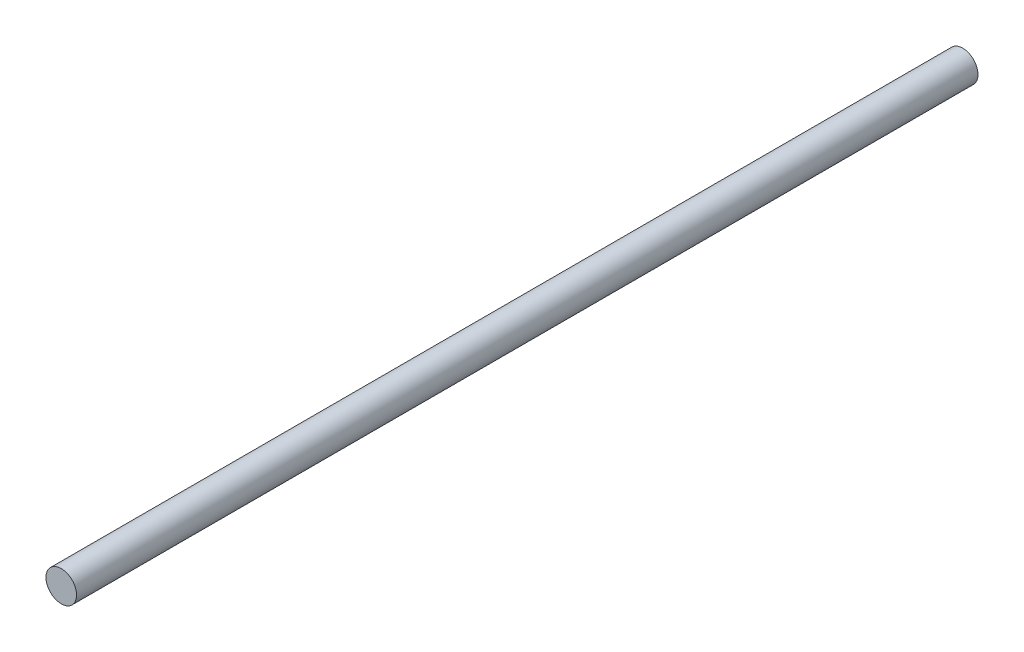
SolidWorks part; units mm, degrees
ref_plane "Ön Düzlem" through (0, 0, 0) normal (0, 0, 1) x (1, 0, 0)
ref_plane "Üst Düzlem" through (0, 0, 0) normal (0, 1, 0) x (1, 0, 0)
ref_plane "Sağ Düzlem" through (0, 0, 0) normal (1, 0, 0) x (0, 0, -1)
sketch "Sketch1" plane through (0, 0, 0) normal (0, 0, 1) x (1, 0, 0)
  circle A0 centre (0, 0) radius 1.95
extrude "Boss-Extrude1" add sketch "Sketch1" along normal blind 115
